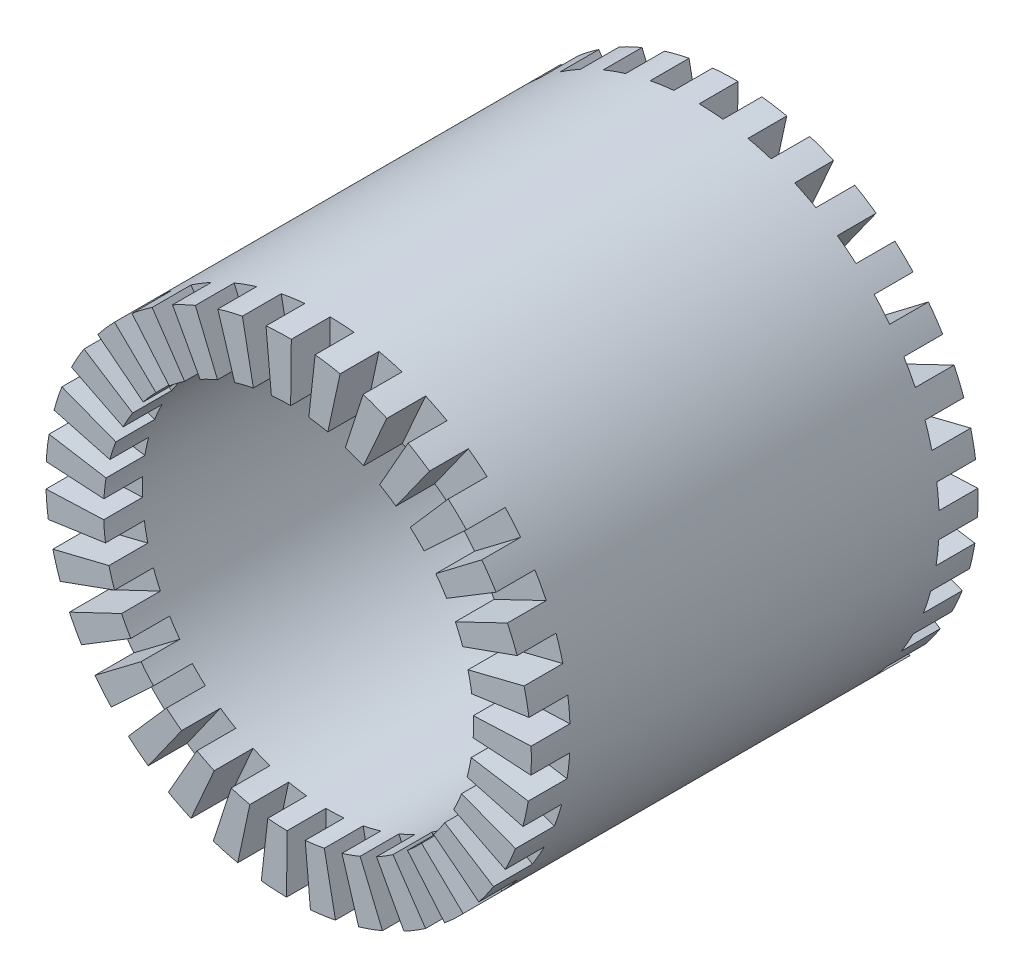
SolidWorks part; units mm, degrees
ref_plane "Front Plane" through (0, 0, 0) normal (1, 0, 0) x (0, 1, 0)
ref_plane "Top Plane" through (0, 0, 0) normal (0, 0, 1) x (0, 1, 0)
ref_plane "Right Plane" through (0, 0, 0) normal (0, 1, 0) x (-1, 0, 0)
sketch "Sketch1" plane through (0, 0, 0) normal (0, 0, 1) x (0, 1, 0)
  circle A0 centre (0, 0) radius 12.5
  circle A1 centre (0, 0) radius 9.525
  dimension "D1" = 25
  dimension "D2" = 19.05
extrude "Boss-Extrude1" add sketch "Sketch1" along normal blind 19
sketch "Sketch2" plane through (0, 0, 19) normal (0, 0, 1) x (1, 0, 0)
  line L0 (-7.4838, 5.8922) -> (-9.8213, 7.7325)
  line L1 (-8.9625, 8.7134) -> (-6.8294, 6.6396)
  circle A0 centre (0, 0) radius 9.525 construction
  circle A1 centre (0, 0) radius 12.5 construction
  arc A4 (-9.8213, 7.7325) -> (-8.9625, 8.7134) centre (0, 0) cw
  arc A5 (-7.4838, 5.8922) -> (-6.8294, 6.6396) centre (0, 0) cw
extrude "Boss-Extrude2" add sketch "Sketch2" along normal blind 2
pattern_circular "CirPattern1" count 31 over 360 about axis through (0, 0, 0) along (0, 0, 1) of "Boss-Extrude2"
ref_plane "Plane1" through (0, 0, 9.5) normal (0, 0, 1) x (0, 1, 0)
mirror "Mirror1" about plane through (0, 0, 9.5) normal (0, 0, 1) of "Boss-Extrude2", "CirPattern1"
